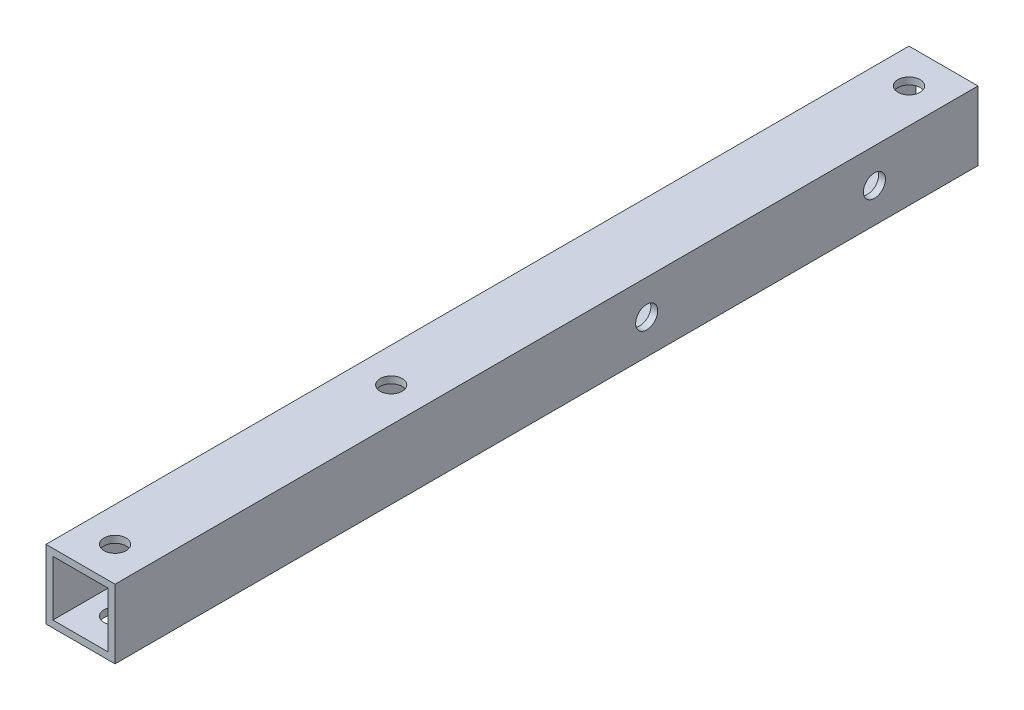
SolidWorks part; units mm, degrees
ref_plane "正面" through (0, 0, 0) normal (0, 0, 1) x (1, 0, 0)
ref_plane "平面" through (0, 0, 0) normal (0, 1, 0) x (1, 0, 0)
ref_plane "右側面" through (0, 0, 0) normal (1, 0, 0) x (0, 0, -1)
sketch "ｽｹｯﾁ1" plane through (0, 0, 0) normal (0, 0, 1) x (1, 0, 0)
  line L0 (-4, 4) -> (-4, -4)
  line L1 (-5, 5) -> (5, 5)
  line L2 (-5, 5) -> (-5, -5)
  line L3 (-5, -5) -> (5, -5)
  line L4 (5, 5) -> (5, -5)
  line L5 (-5, 5) -> (5, -5) construction
  line L6 (-5, -5) -> (5, 5) construction
  line L7 (-4, -4) -> (4, -4)
  line L8 (4, 4) -> (4, -4)
  line L9 (-4, 4) -> (4, 4)
  point P0 (0, 0)
  dimension "D1" = 10
  dimension "D2" = 10
  dimension "D3" = 1
extrude "ﾎﾞｽ - 押し出し1" add sketch "ｽｹｯﾁ1" along normal blind 125
sketch "ｽｹｯﾁ2" plane through (0, -5, 0) normal (0, -1, 0) x (1, 0, 0)
  line L0 (0, -5.5) -> (0, 5.5) construction
  line L1 (5.5, 0) -> (-5.5, 0) construction
  circle A0 centre (0, 5) radius 1.6
  circle A1 centre (0, 80) radius 1.6
  circle A2 centre (0, 120) radius 1.6
  dimension "D1" = 3.2
  dimension "D2" = 5
  dimension "D3" = 3.2
  dimension "D4" = 3.2
  dimension "D5" = 40
  dimension "D6" = 80
extrude "ｶｯﾄ - 押し出し1" cut sketch "ｽｹｯﾁ2" against normal through all
sketch "ｽｹｯﾁ3" plane through (5, 0, 0) normal (1, 0, 0) x (0, 0, -1)
  line L0 (5.5, 0) -> (-5.5, 0) construction
  line L1 (0, 5.5) -> (0, -5.5) construction
  circle A0 centre (-15, 0) radius 1.6
  dimension "D1" = 3.2
  dimension "D2" = 15
extrude "ｶｯﾄ - 押し出し2" cut sketch "ｽｹｯﾁ3" against normal through all
sketch "ｽｹｯﾁ4" plane through (5, 0, 0) normal (1, 0, 0) x (0, 0, -1)
  circle A0 centre (-47.9899, 0) radius 1.6
  dimension "D1" = 3.2
extrude "ｶｯﾄ - 押し出し3" cut sketch "ｽｹｯﾁ4" against normal through all
